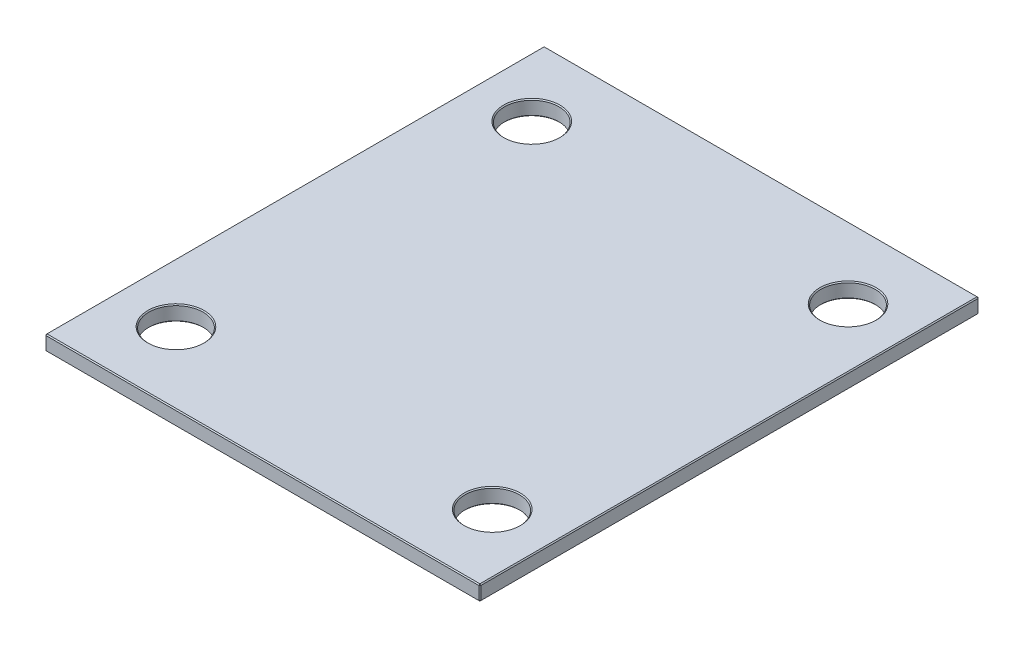
SolidWorks part; units mm, degrees
material "AISI 304"
ref_plane "Front Plane" through (0, 0, 0) normal (0, 0, 1) x (1, 0, 0)
ref_plane "Top Plane" through (0, 0, 0) normal (0, 1, 0) x (1, 0, 0)
ref_plane "Right Plane" through (0, 0, 0) normal (1, 0, 0) x (0, 0, -1)
sketch "Sketch1" plane through (0, 0, 0) normal (0, 1, 0) x (1, 0, 0)
  line L0 (-22, 25.25) -> (-22, 18) construction
  line L1 (-22, 25.25) -> (22, 25.25)
  line L2 (-22, 25.25) -> (-22, -25.25)
  line L3 (-22, -25.25) -> (22, -25.25)
  line L4 (22, 25.25) -> (22, -25.25)
  line L5 (-22, 25.25) -> (22, -25.25) construction
  line L6 (-22, -25.25) -> (22, 25.25) construction
  line L7 (-22, 18) -> (-16, 18) construction
  line L8 (22, 25.25) -> (22, 18) construction
  line L9 (22, 18) -> (16, 18) construction
  line L10 (-22, -25.25) -> (-22, -18) construction
  line L11 (-22, -18) -> (-16, -18) construction
  line L12 (22, -25.25) -> (21.9576, -25.25)
  line L13 (21.9576, -25.25) -> (22, -18.0001) construction
  line L14 (22, -18.0001) -> (16, -18.0001) construction
  circle A0 centre (-16, 18) radius 2.75
  circle A1 centre (16, 18) radius 2.75
  circle A2 centre (16, -18.0001) radius 2.75
  circle A3 centre (-16, -18) radius 2.75
  point P0 (0, 0)
  dimension "D5" = 5.5
  dimension "D1" = 44
  dimension "D2" = 50.5
  dimension "D3" = 6
  dimension "D4" = 7.25
extrude "Boss-Extrude1" add sketch "Sketch1" along normal blind 1.524 contours L4 L1 L2 L3 A3 A2 A1 A0
chamfer "Chamfer1" distance 0.1 angle 45 20 edges at (22, 0, 0) (22, 0.762, 25.25) (0, 0, 25.25) (0, 1.524, 25.25) (-22, 0.762, 25.25) (-22, 0, 0) (0, 0, -25.25) (-22, 0.762, -25.25) (-22, 1.524, 0) (22, 1.524, 0) (0, 1.524, -25.25) (22, 0.762, -25.25) (16, 0, -15.25) (16, 1.524, -15.25) (-16, 0, -15.25) (-16, 1.524, -15.25) (-16, 0, 20.75) (-16, 1.524, 20.75) (16, 0, 20.7501) (16, 1.524, 20.7501)
